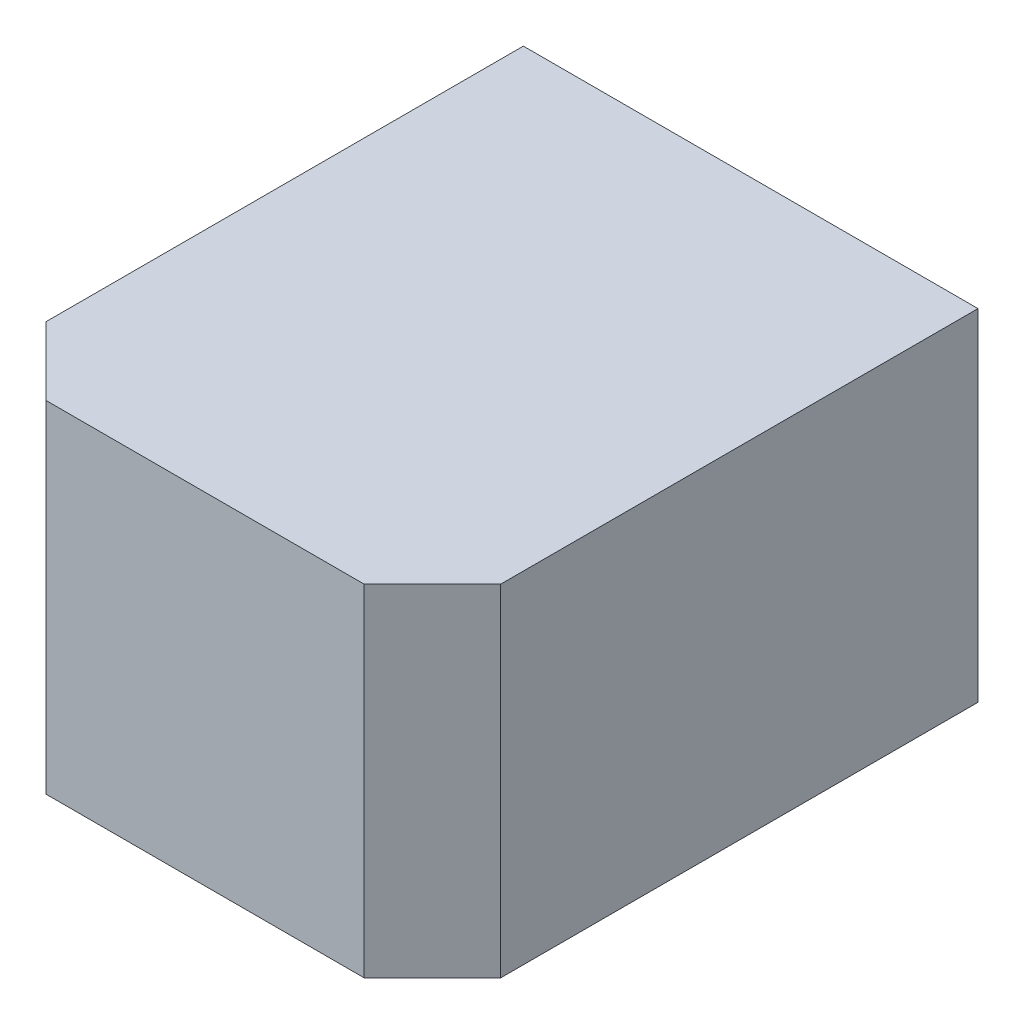
SolidWorks part; units mm, degrees
ref_plane "Front Plane" through (0, 0, 0) normal (0, 0, 1) x (1, 0, 0)
ref_plane "Top Plane" through (0, 0, 0) normal (0, 1, 0) x (1, 0, 0)
ref_plane "Right Plane" through (0, 0, 0) normal (1, 0, 0) x (0, 0, -1)
sketch "Sketch1" plane through (0, 0, 0) normal (0, 0, 1) x (1, 0, 0)
  line L1 (-10, 7.5) -> (10, 7.5)
  line L2 (-10, 7.5) -> (-10, -7.5)
  line L3 (-10, -7.5) -> (10, -7.5)
  line L4 (10, 7.5) -> (10, -7.5)
  line L5 (-10, 7.5) -> (10, -7.5) construction
  line L6 (-10, -7.5) -> (10, 7.5) construction
  point P0 (0, 0)
  dimension "D1" = 15
  dimension "D2" = 20
extrude "Boss-Extrude1" add sketch "Sketch1" along normal blind 24
chamfer "Chamfer2" distance 3 angle 45 1 edges at (10, 0, 24)
chamfer "Chamfer3" distance 3 angle 45 1 edges at (-10, 0, 24)
sketch "Sketch3" plane through (0, 0, 0) normal (0, 0, -1) x (-1, 0, 0)
  line L0 (3.1225, 2.5) -> (3.1225, -2.5)
  circle A0 centre (0, 0) radius 4
  arc A1 (3.1225, 2.5) -> (3.1225, -2.5) centre (0, 0) ccw
  dimension "D1" = 8
  dimension "D2" = 5
extrude "Cut-Extrude1" cut sketch "Sketch3" against normal blind 10 contours L0 A0
